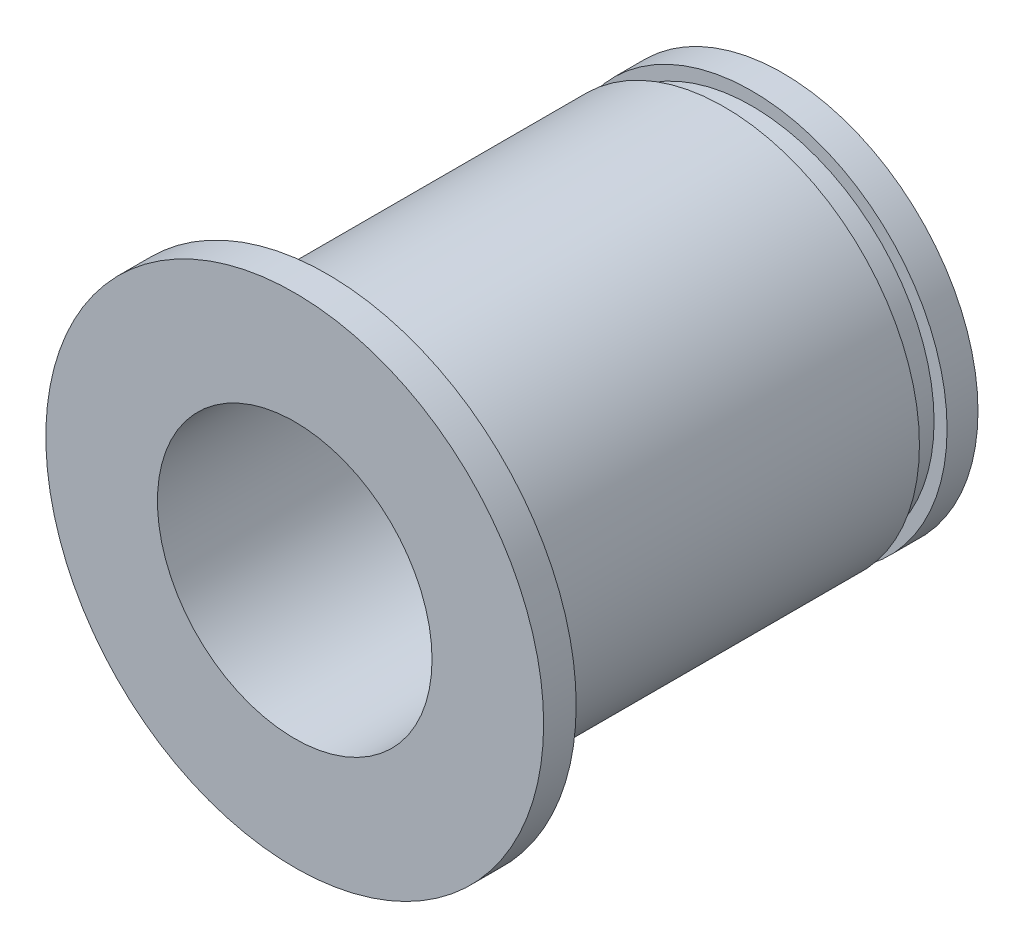
SolidWorks part; units mm, degrees
ref_plane "Front Plane" through (0, 0, 0) normal (0, 0, 1) x (1, 0, 0)
ref_plane "Top Plane" through (0, 0, 0) normal (0, 1, 0) x (1, 0, 0)
ref_plane "Right Plane" through (0, 0, 0) normal (1, 0, 0) x (0, 0, -1)
sketch "S01 - Ground guide bore and body" plane through (0, 0, 0) normal (0, 0, 1) x (1, 0, 0)
  circle A0 centre (0, 0) radius 6
  circle A1 centre (0, 0) radius 4.22
  dimension "D1" = 8.44
  dimension "D2" = 12
extrude "01 - Ground guide bore and body" add sketch "S01 - Ground guide bore and body" along normal blind 14 from offset 2
sketch "S02 - Outboard flange" plane through (0, 0, 0) normal (0, 0, 1) x (1, 0, 0)
  circle A0 centre (0, 0) radius 7.65
  circle A1 centre (0, 0) radius 4.22
  dimension "D1" = 8.44
  dimension "D2" = 15.3
extrude "02 - Outboard flange" add sketch "S02 - Outboard flange" along normal blind 1 from offset 12
sketch "S03 - External retaining ring groove" plane through (0, 0, 0) normal (0, 0, 1) x (1, 0, 0)
  circle A0 centre (0, 0) radius 6.1
  circle A1 centre (0, 0) radius 5.6
  dimension "D1" = 11.2
  dimension "D2" = 12.2
extrude "03 - External retaining ring groove" cut sketch "S03 - External retaining ring groove" along normal blind 0.85 from offset 1.05
